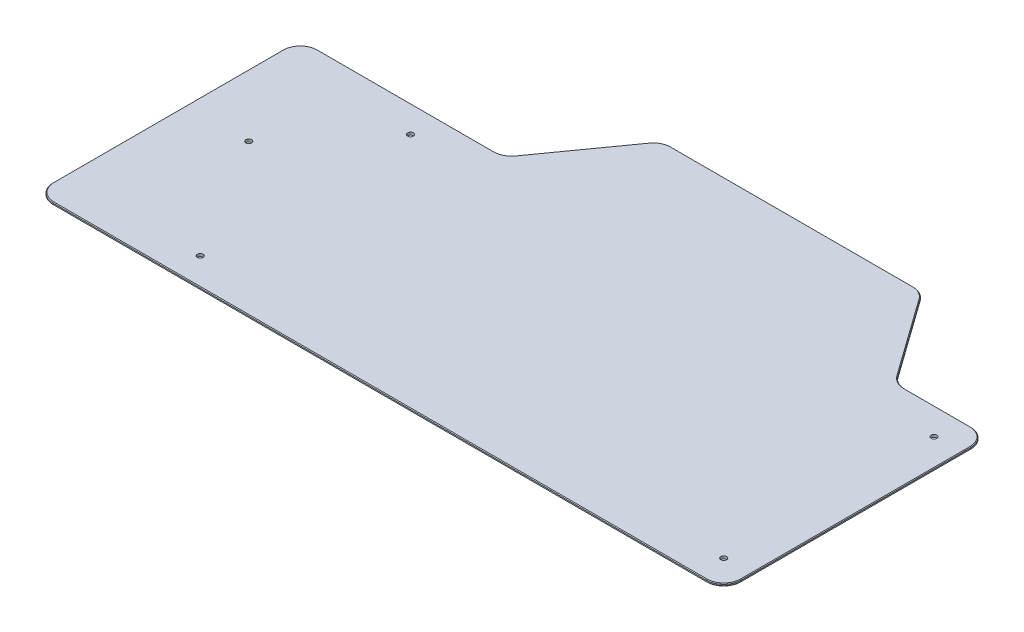
SolidWorks part; units mm, degrees
ref_plane "前视基准面" through (0, 0, 0) normal (0, 0, 1) x (1, 0, 0)
ref_plane "上视基准面" through (0, 0, 0) normal (0, 1, 0) x (1, 0, 0)
ref_plane "右视基准面" through (0, 0, 0) normal (1, 0, 0) x (0, 0, -1)
other "Configuration Table"
sketch "草图1" plane through (0, 0, 0) normal (0, 1, 0) x (1, 0, 0)
  line L0 (305, 405) -> (230, 300)
  line L1 (0, 0) -> (780, 0)
  line L2 (0, 0) -> (0, 300)
  line L3 (0, 300) -> (780, 300)
  line L4 (780, 0) -> (780, 300)
  line L5 (305, 300) -> (600, 300)
  line L7 (305, 405) -> (600, 405)
  line L9 (600, 405) -> (675, 300)
  dimension "D1" = 780
  dimension "D2" = 300
  dimension "D3" = 295
  dimension "D4" = 105
  dimension "D6" = 75
  dimension "D7" = 75
extrude "凸台-拉伸1" add sketch "草图1" along normal blind 3
fillet "圆角3" radius 20 8 edges at (0, 1.5, 0) (0, 1.5, -300) (230, 1.5, -300) (305, 1.5, -405) (600, 1.5, -405) (675, 1.5, -300) (780, 1.5, -300) (780, 1.5, 0)
chamfer "倒角1" distance 0.8 angle 45 32 edges at (774.1421, 3, -5.8579) (774.1421, 0, -5.8579) (780, 0, -150) (780, 3, -150) (774.1421, 3, -294.1421) (774.1421, 0, -294.1421) (119.8538, 3, -300) (119.8538, 0, -300) (676.1407, 3, -302.2166) (676.1407, 0, -302.2166) (637.5, 0, -352.5) (637.5, 3, -352.5) (598.8593, 3, -402.7834) (598.8593, 0, -402.7834) (452.5, 0, -405) (452.5, 3, -405) (306.1407, 3, -402.7834) (306.1407, 0, -402.7834) (267.5, 0, -352.5) (267.5, 3, -352.5) (228.8593, 3, -302.2166) (228.8593, 0, -302.2166) (722.6462, 0, -300) (722.6462, 3, -300) (5.8579, 3, -294.1421) (5.8579, 0, -294.1421) (0, 0, -150) (0, 3, -150) (5.8579, 3, -5.8579) (5.8579, 0, -5.8579) (390, 3, 0) (390, 0, 0)
sketch "草图2" plane through (0, 3, 0) normal (0, 1, 0) x (1, 0, 0)
  line L0 (20, 0.8) -> (760, 0.8) construction
  line L1 (0.8, 280) -> (0.8, 20) construction
  line L2 (779.2, 150) -> (405.257, 150) construction
  line L3 (779.2, 20) -> (779.2, 280) construction
  line L4 (452.5, 404.2) -> (452.5, 255.0821) construction
  line L5 (589.7076, 404.2) -> (315.2924, 404.2) construction
  line L6 (760, 299.2) -> (685.2924, 299.2) construction
  circle A0 centre (70.8, 170.8) radius 3.25
  circle A1 centre (749.2, 269.2) radius 3.25
  circle A2 centre (749.2, 30.8) radius 3.25
  circle A3 centre (155.8, 30.8) radius 3.25
  circle A4 centre (155.8, 269.2) radius 3.25
  dimension "D1" = 6.5
  dimension "D2" = 170
  dimension "D3" = 70
  dimension "D4" = 6.5
  dimension "D5" = 30
  dimension "D6" = 30
extrude "切除-拉伸1" cut sketch "草图2" against normal blind 10
equation "\"D7@草图1\"=\"D6@草图1\""
